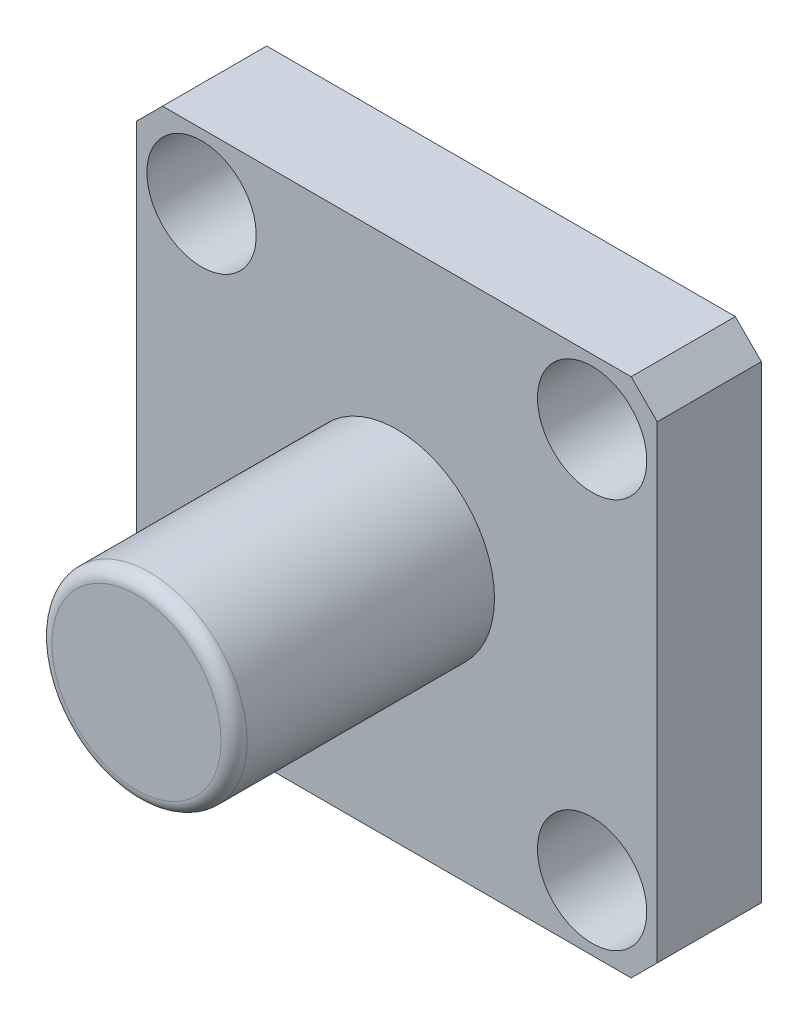
SolidWorks part; units mm, degrees
ref_plane "前视基准面" through (0, 0, 0) normal (0, 0, 1) x (1, 0, 0)
ref_plane "上视基准面" through (0, 0, 0) normal (0, 1, 0) x (1, 0, 0)
ref_plane "右视基准面" through (0, 0, 0) normal (1, 0, 0) x (0, 0, -1)
other "Configuration Table"
sketch "草图1" plane through (0, 0, 0) normal (0, 0, 1) x (1, 0, 0)
  line L1 (-10, -10) -> (10, -10)
  line L2 (-10, -10) -> (-10, 10)
  line L3 (-10, 10) -> (10, 10)
  line L4 (10, -10) -> (10, 10)
  line L5 (-10, -10) -> (10, 10) construction
  line L6 (-10, 10) -> (10, -10) construction
  point P0 (0, 0)
  dimension "D1" = 20
  dimension "D2" = 20
extrude "凸台-拉伸1" add sketch "草图1" along normal blind 4
sketch "草图2" plane through (0, 0, 4) normal (0, 0, 1) x (1, 0, 0)
  circle A0 centre (0, 0) radius 3.75
  dimension "D1" = 7.5
extrude "凸台-拉伸2" add sketch "草图2" along normal blind 10
sketch "草图3" plane through (0, 0, 0) normal (0, 0, -1) x (-1, 0, 0)
  line L1 (-7.5, -7.5) -> (7.5, -7.5) construction
  line L2 (-7.5, -7.5) -> (-7.5, 7.5) construction
  line L3 (-7.5, 7.5) -> (7.5, 7.5) construction
  line L4 (7.5, -7.5) -> (7.5, 7.5) construction
  line L5 (-7.5, -7.5) -> (7.5, 7.5) construction
  line L6 (-7.5, 7.5) -> (7.5, -7.5) construction
  point P0 (0, 0)
  dimension "D1" = 15
  dimension "D2" = 15
hole_wizard "Ø4.2 (4.2) 直径孔1" positions "3D草图1" profile "草图4" hole size "Ø4.2" standard "GB" end condition through all
sketch3d "3D草图1"
  point P0 (7.5, 7.5, 0)
  point P3 (-7.5, 7.5, 0)
  point P6 (-7.5, -7.5, 0)
  point P9 (7.5, -7.5, 0)
sketch "草图4" plane through (7.5, 7.5, 0) normal (1, 0, 0) x (0, 1, 0)
  line L0 (0, 0) -> (0, 14)
  line L1 (0, 14) -> (2.1, 14)
  line L2 (2.1, 14) -> (2.1, 0.025)
  line L3 (2.1, 0.025) -> (2.125, 0)
  line L5 (2.125, 0) -> (0, 0)
  line L6 (-2.1, 0.025) -> (-2.125, 0) construction
  line L11 (0, -6.35) -> (0, 107.95) construction
  dimension "通孔孔直径" = 4.2
  dimension "通孔孔深度" = 14
  dimension "近端锥形沉头孔直径" = 4.25
  dimension "近端锥形沉头孔角度" = 90
fillet "圆角1" radius 0.5 1 edges at (3.75, 0, 14)
chamfer "倒角1" distance 1 angle 45 4 edges at (-10, -10, 2) (10, -10, 2) (10, 10, 2) (-10, 10, 2)
